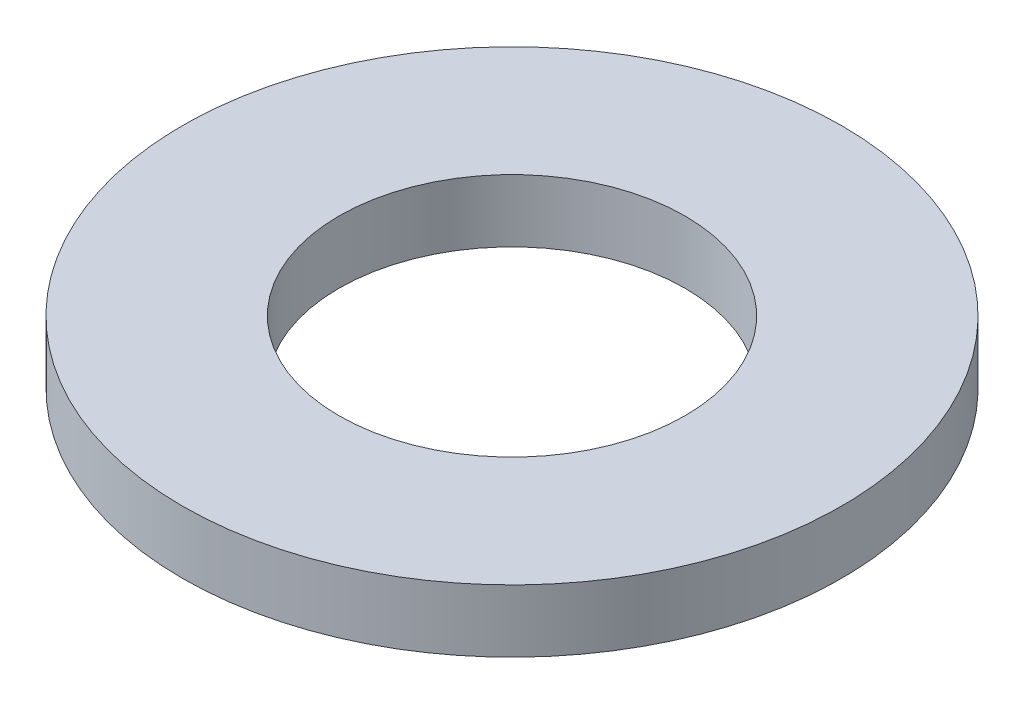
SolidWorks part; units mm, degrees
material "Galvanized Steel"
ref_plane "Front Plane" through (0, 0, 0) normal (0, 0, 1) x (1, 0, 0)
ref_plane "Top Plane" through (0, 0, 0) normal (0, 1, 0) x (1, 0, 0)
ref_plane "Right Plane" through (0, 0, 0) normal (1, 0, 0) x (0, 0, -1)
sketch "Sketch2" plane through (0, 0, 0) normal (0, 1, 0) x (1, 0, 0)
  circle A0 centre (0, 0) radius 10
  circle A1 centre (0, 0) radius 5.25
  dimension "D1" = 10.5
  dimension "D2" = 20
extrude "Boss-Extrude1" add sketch "Sketch2" along normal mid plane 1.9
